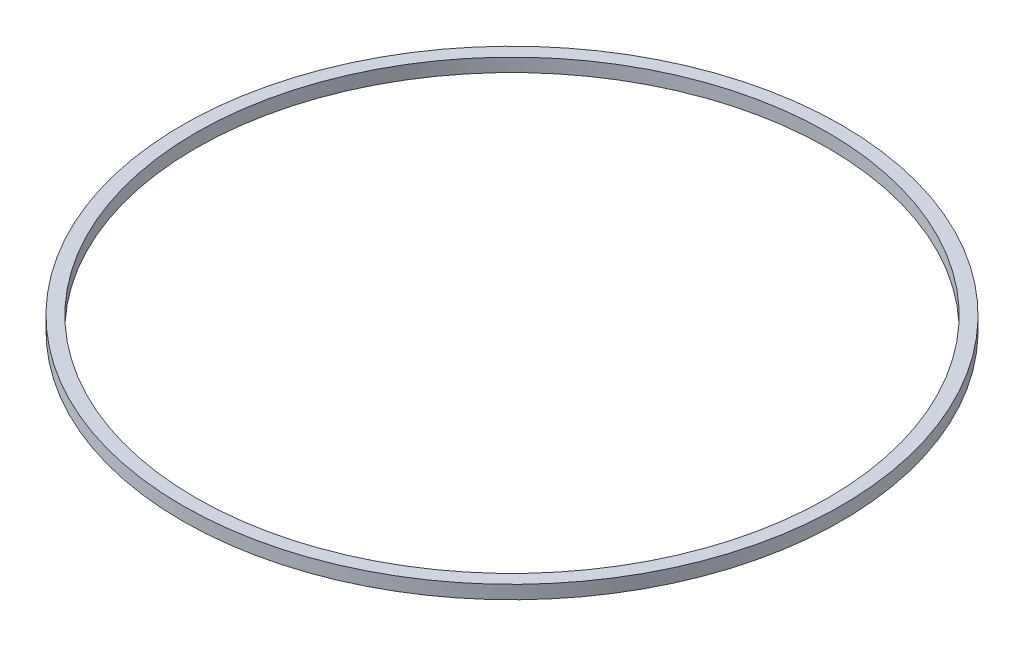
SolidWorks part; units mm, degrees
ref_plane "Front Plane" through (0, 0, 0) normal (0, 0, 1) x (1, 0, 0)
ref_plane "Top Plane" through (0, 0, 0) normal (0, 1, 0) x (1, 0, 0)
ref_plane "Right Plane" through (0, 0, 0) normal (1, 0, 0) x (0, 0, -1)
sketch "Sketch1" plane through (0, 0, 0) normal (0, 0, 1) x (1, 0, 0)
  line L0 (0, 0) -> (0, 3.2414) construction
  line L2 (-50.1338, 0) -> (-52.2551, 0)
  line L3 (-52.2551, 0) -> (-52.2551, 2.1213)
  line L4 (-52.2551, 2.1213) -> (-50.1338, 2.1213)
  line L5 (-50.1338, 2.1213) -> (-50.1338, 0)
  point P3 (0, 0)
  dimension "D1" = 50.1338
  dimension "D2" = 3
revolve "Revolve1" add sketch "Sketch1" angle 360 about L0
